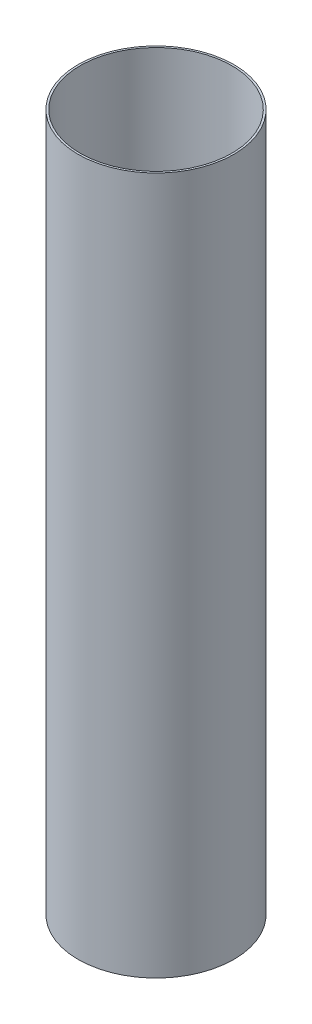
SolidWorks part; units mm, degrees
material "A-Glass Fiber"
ref_plane "Front Plane" through (0, 0, 0) normal (0, 0, 1) x (1, 0, 0)
ref_plane "Top Plane" through (0, 0, 0) normal (0, 1, 0) x (1, 0, 0)
ref_plane "Right Plane" through (0, 0, 0) normal (1, 0, 0) x (0, 0, -1)
sketch "Sketch1" plane through (0, 0, 0) normal (0, 0, 1) x (1, 0, 0)
  line L0 (78.16, 0) -> (78.16, 700)
  line L1 (76.2, 0) -> (76.2, 700)
  line L2 (78.16, 700) -> (76.2, 700)
  line L3 (76.2, 0) -> (78.16, 0)
  line L4 (0, 204.6154) -> (0, 85.8935) construction
  dimension "D1" = 76.2
  dimension "D2" = 700
  dimension "D3" = 1.96
revolve "Revolve1" add sketch "Sketch1" angle 360 about L4
